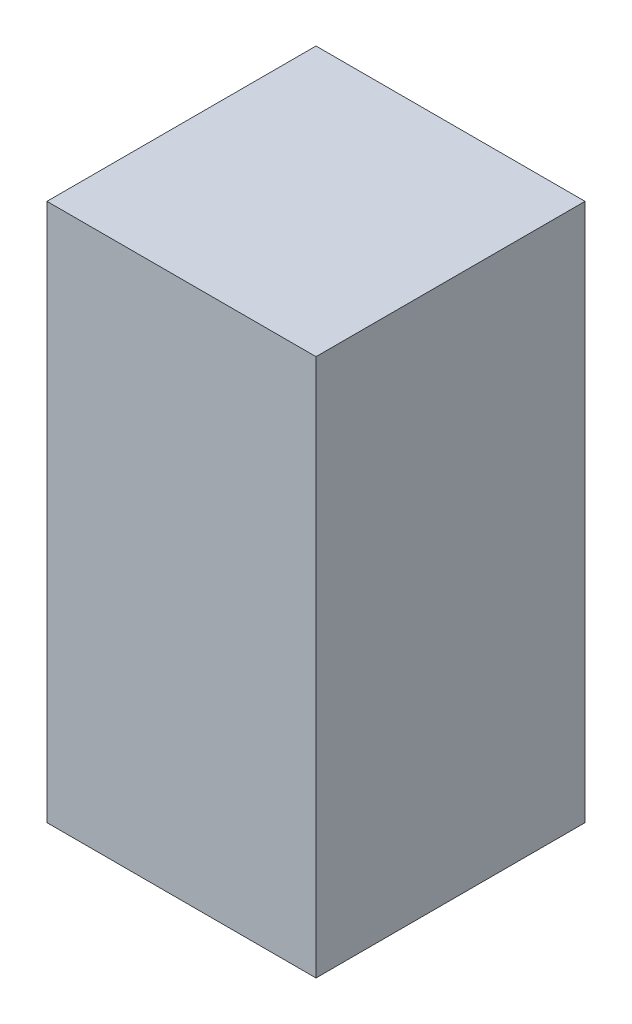
SolidWorks part; units mm, degrees
ref_plane "Front Plane" through (0, 0, 0) normal (0, 0, 1) x (1, 0, 0)
ref_plane "Top Plane" through (0, 0, 0) normal (0, 1, 0) x (1, 0, 0)
ref_plane "Right Plane" through (0, 0, 0) normal (1, 0, 0) x (0, 0, -1)
sketch "Sketch1" plane through (0, 0, 0) normal (0, 0, 1) x (1, 0, 0)
  line L1 (5, -10) -> (-5, -10)
  line L2 (5, -10) -> (5, 10)
  line L3 (5, 10) -> (-5, 10)
  line L4 (-5, -10) -> (-5, 10)
  line L5 (5, -10) -> (-5, 10) construction
  line L6 (5, 10) -> (-5, -10) construction
  point P0 (0, 0)
  dimension "D1" = 10
  dimension "D2" = 20
extrude "Boss-Extrude1" add sketch "Sketch1" along normal mid plane 10
